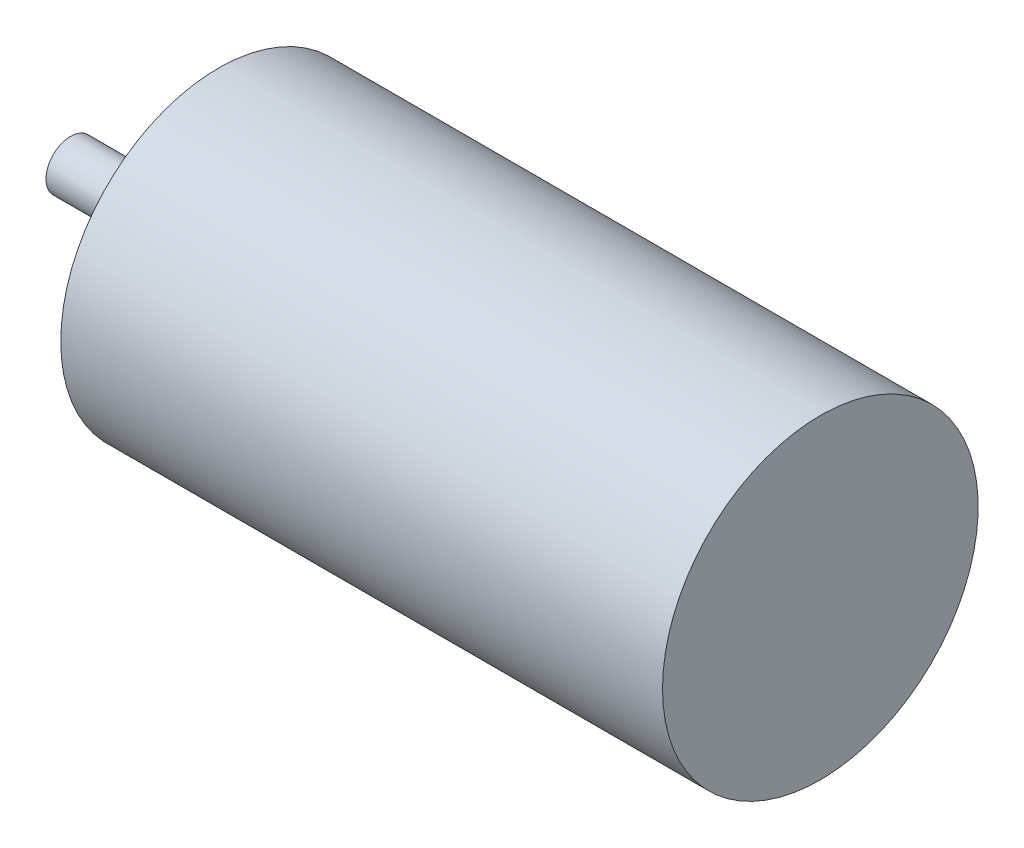
SolidWorks part; units mm, degrees
ref_plane "前视基准面" through (0, 0, 0) normal (0, 0, 1) x (1, 0, 0)
ref_plane "上视基准面" through (0, 0, 0) normal (0, 1, 0) x (1, 0, 0)
ref_plane "右视基准面" through (0, 0, 0) normal (1, 0, 0) x (0, 0, -1)
sketch "Sketch1" plane through (0, 0, 0) normal (1, 0, 0) x (0, 0, -1)
  circle A0 centre (0, 0) radius 16
extrude "Boss-Extrude1" add sketch "Sketch1" along normal blind 61
sketch "Sketch2" plane through (0, 0, 0) normal (-1, 0, 0) x (0, 0, 1)
  circle A0 centre (0, 0) radius 11
extrude "Boss-Extrude2" add sketch "Sketch2" along normal blind 2
sketch "Sketch3" plane through (0, 0, 0) normal (-1, 0, 0) x (0, 0, 1)
  circle A0 centre (0, 0) radius 13.5 construction
  circle A1 centre (0, 13.5) radius 1.5
  circle A2 centre (11.6913, 6.75) radius 1.5
  circle A3 centre (11.6913, -6.75) radius 1.5
  circle A4 centre (0, -13.5) radius 1.5
  circle A5 centre (-11.6913, -6.75) radius 1.5
  circle A6 centre (-11.6913, 6.75) radius 1.5
  dimension "D1" = 6
extrude "Cut-Extrude1" cut sketch "Sketch3" against normal blind 4
sketch "Sketch4" plane through (-2, 0, 0) normal (-1, 0, 0) x (0, 0, 1)
  circle A0 centre (0, 0) radius 2.5
  dimension "D1" = 5
extrude "Boss-Extrude3" add sketch "Sketch4" along normal blind 13
